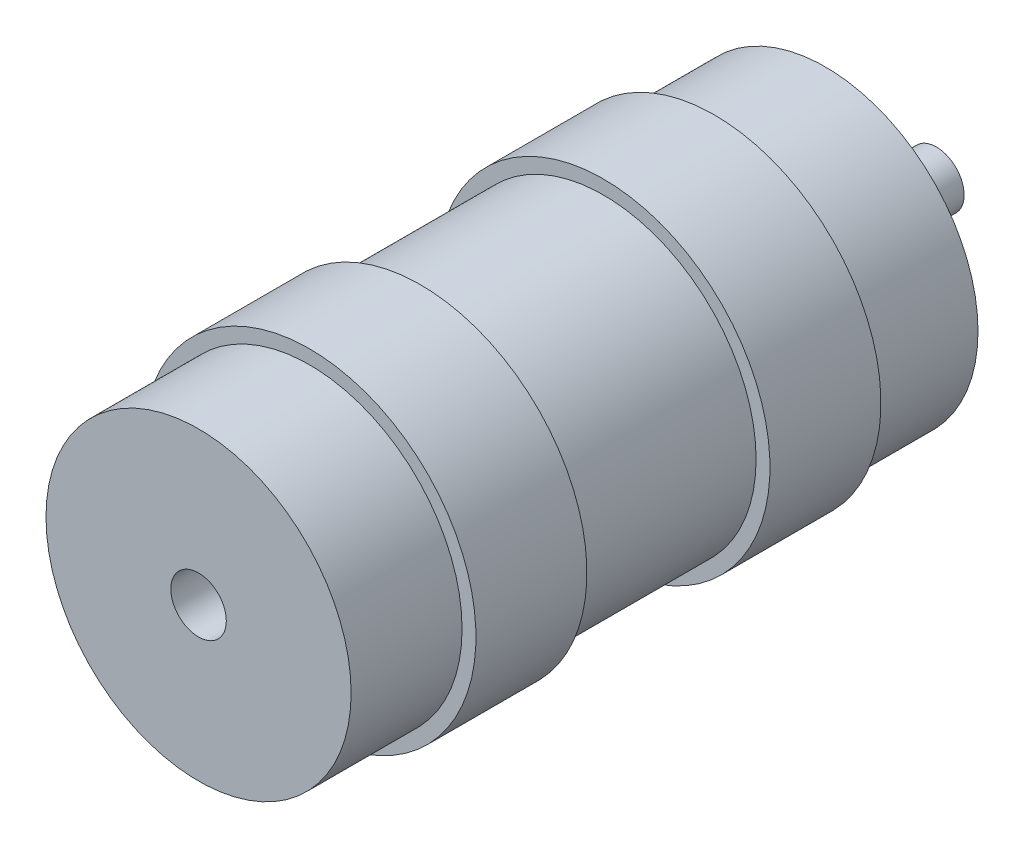
SolidWorks part; units mm, degrees
ref_plane "Front Plane" through (0, 0, 0) normal (0, 0, 1) x (1, 0, 0)
ref_plane "Top Plane" through (0, 0, 0) normal (0, 1, 0) x (1, 0, 0)
ref_plane "Right Plane" through (0, 0, 0) normal (1, 0, 0) x (0, 0, -1)
sketch "Sketch1" plane through (0, 0, 0) normal (0, 0, 1) x (1, 0, 0)
  circle A0 centre (0, 0) radius 5
  dimension "D1" = 10
extrude "Boss-Extrude1" add sketch "Sketch1" along normal blind 20 contours A0
sketch "Sketch2" plane through (0, 0, 20) normal (0, 0, 1) x (1, 0, 0)
  circle A0 centre (0, 0) radius 27.5
  dimension "D1" = 55
extrude "Boss-Extrude2" add sketch "Sketch2" along normal blind 113
ref_plane "Plane1" through (0, 0, 50) normal (0, 0, -1) x (-1, 0, 0)
ref_plane "Plane2" through (0, 0, 103) normal (0, 0, -1) x (-1, 0, 0)
ref_plane "Plane3" through (0, 0, 133) normal (0, 0, -1) x (-1, 0, 0)
sketch "Sketch3" plane through (0, 0, 50) normal (0, 0, -1) x (-1, 0, 0)
  circle A0 centre (0, 0) radius 30
  dimension "D1" = 60
extrude "Boss-Extrude3" add sketch "Sketch3" along normal blind 10 and the other way blind 10
sketch "Sketch4" plane through (0, 0, 103) normal (0, 0, -1) x (-1, 0, 0)
  circle A0 centre (0, 0) radius 30
  circle A1 centre (0, 0) radius 30 construction
extrude "Boss-Extrude4" add sketch "Sketch4" along normal blind 10 and the other way blind 10
sketch "Sketch5" plane through (0, 0, 133) normal (0, 0, 1) x (1, 0, 0)
  circle A0 centre (0, 0) radius 5
  dimension "D1" = 10
extrude "Cut-Extrude1" cut sketch "Sketch5" against normal blind 20
